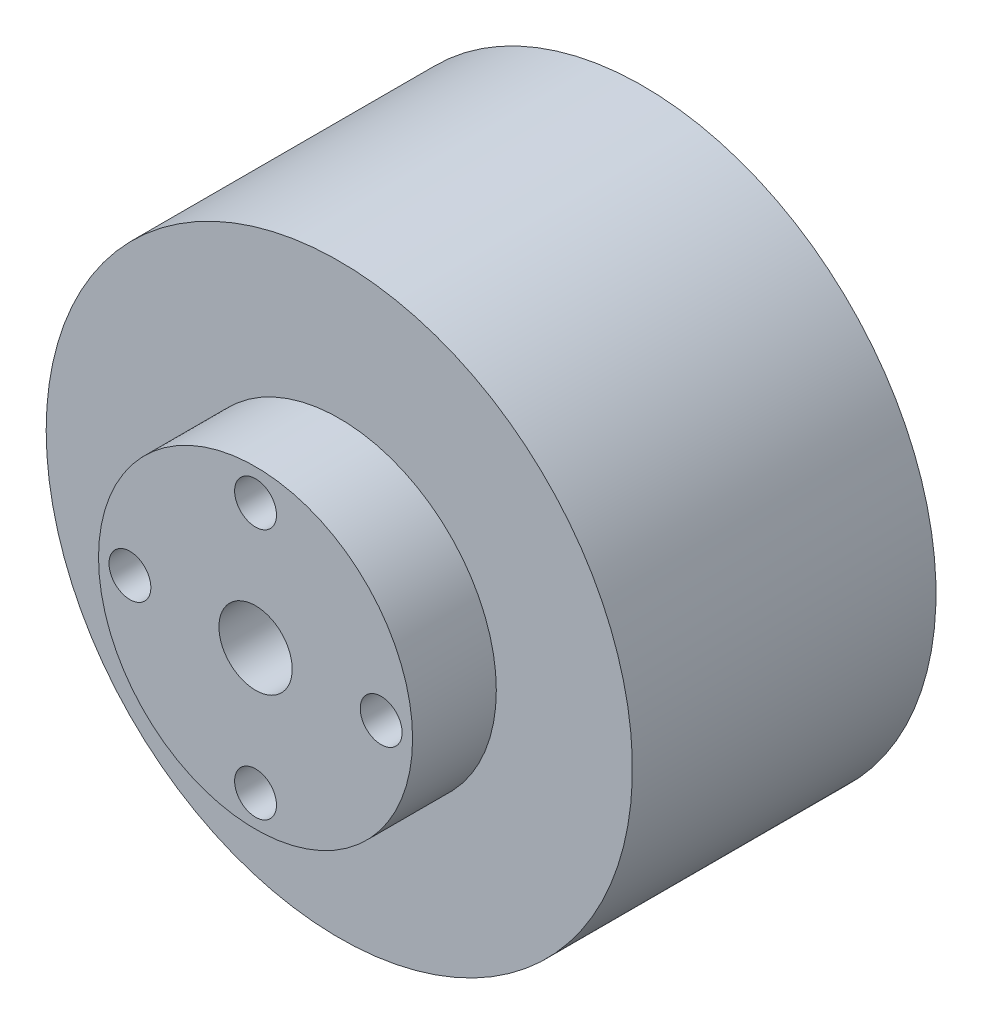
SolidWorks part; units mm, degrees
ref_plane "前视基准面" through (0, 0, 0) normal (0, 0, 1) x (1, 0, 0)
ref_plane "上视基准面" through (0, 0, 0) normal (0, 1, 0) x (1, 0, 0)
ref_plane "右视基准面" through (0, 0, 0) normal (1, 0, 0) x (0, 0, -1)
sketch "草图1" plane through (0, 0, 0) normal (0, 0, 1) x (1, 0, 0)
  circle A0 centre (0, 0) radius 14
  dimension "D1" = 28
extrude "凸台-拉伸1" add sketch "草图1" along normal blind 14.5
sketch "草图3" plane through (0, 0, 14.5) normal (0, 0, 1) x (1, 0, 0)
  circle A0 centre (0, 0) radius 7.5
  dimension "D1" = 15
extrude "凸台-拉伸3" add sketch "草图3" along normal blind 4
sketch "草图4" plane through (0, 0, 18.5) normal (0, 0, 1) x (1, 0, 0)
  circle A0 centre (0, 0) radius 1.75
  dimension "D1" = 3.5
extrude "切除-拉伸1" cut sketch "草图4" against normal through all
sketch "草图5" plane through (0, 0, 18.5) normal (0, 0, 1) x (1, 0, 0)
  line L0 (-17.4028, 0) -> (19.2585, 0) construction
  line L1 (0, 18.129) -> (0, -19.9613) construction
  circle A0 centre (0, -6) radius 1
  circle A1 centre (-6, 0) radius 1
  circle A2 centre (0, 6) radius 1
  circle A3 centre (6, 0) radius 1
  dimension "D1" = 2
  dimension "D2" = 6
  dimension "D3" = 6
  dimension "D4" = 6
  dimension "D5" = 6
extrude "切除-拉伸2" cut sketch "草图5" against normal blind 3 contours A3 | A1 | A0 | A2
sketch "草图6" plane through (0, 0, 0) normal (0, 0, 1) x (1, 0, 0)
  line L0 (24.9097, 0) -> (-28.6773, 0) construction
  line L1 (0, 19.7976) -> (0, -23.3744) construction
  circle A0 centre (0, 8) radius 1.5
  circle A1 centre (-8, 0) radius 1.5
  circle A2 centre (0, -8) radius 1.5
  circle A3 centre (8, 0) radius 1.5
  dimension "D1" = 3
  dimension "D2" = 8
  dimension "D3" = 8
  dimension "D4" = 8
  dimension "D5" = 8
extrude "切除-拉伸3" cut sketch "草图6" along normal blind 3
